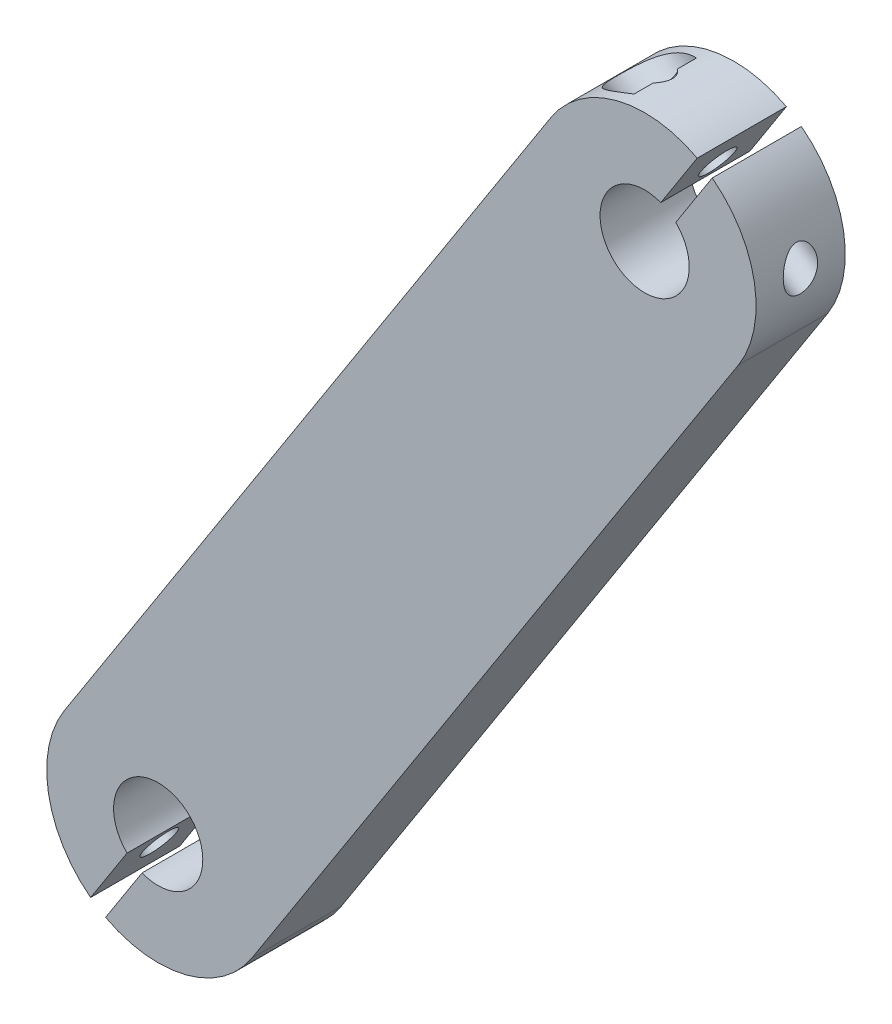
SolidWorks part; units mm, degrees
material "ALUMINUM 6061"
ref_plane "Front Plane" through (0, 0, 0) normal (0, 0, 1) x (1, 0, 0)
ref_plane "Top Plane" through (0, 0, 0) normal (0, 1, 0) x (1, 0, 0)
ref_plane "Right Plane" through (0, 0, 0) normal (1, 0, 0) x (0, 0, -1)
sketch "Sketch1" plane through (0, 0, 0) normal (0, 0, 1) x (1, 0, 0)
  line L0 (0, 0) -> (0, 177.8) construction
  line L3 (0, 177.8) -> (177.8, 177.8) construction
  line L4 (54.2644, 123.9224) -> (-25.4, 0) construction
  line L5 (54.2644, 123.9224) -> (88.9, 177.8) construction
  line L6 (47.5876, 128.2147) -> (82.2231, 182.0923)
  line L7 (60.9413, 119.6301) -> (95.5769, 173.5077)
  line L8 (-25.4, 0) -> (0, 0) construction
  arc A4 (47.5876, 128.2147) -> (60.9413, 119.6301) centre (54.2644, 123.9224) ccw
  arc A5 (95.5769, 173.5077) -> (82.2231, 182.0923) centre (88.9, 177.8) ccw
  circle A6 centre (88.9, 177.8) radius 3.175
  circle A7 centre (54.2644, 123.9224) radius 3.175
  point P2 (71.5822, 150.8612)
  dimension "D6" = 147.32
  dimension "D3" = 15.875
  dimension "D4" = 6.35
  dimension "D1" = 177.8
  dimension "D2" = 177.8
  dimension "D5" = 25.4
extrude "Boss-Extrude1" add sketch "Sketch1" along normal blind 6.35
sketch "Sketch2" plane through (0, 0, 6.35) normal (0, 0, 1) x (1, 0, 0)
  line L0 (92.6444, 184.7988) -> (90.0481, 180.7602)
  line L1 (91.1164, 180.0734) -> (93.7127, 184.1121)
  line L2 (52.048, 121.649) -> (49.4518, 117.6103)
  line L3 (53.1163, 120.9623) -> (50.5201, 116.9236)
  line L4 (82.2231, 182.0923) -> (47.5876, 128.2147) construction
  arc A4 (95.5769, 173.5077) -> (82.2231, 182.0923) centre (88.9, 177.8) ccw construction
  circle A5 centre (88.9, 177.8) radius 3.175 construction
  circle A6 centre (54.2644, 123.9224) radius 3.175 construction
  arc A7 (47.5876, 128.2147) -> (60.9413, 119.6301) centre (54.2644, 123.9224) ccw construction
  arc A8 (93.7127, 184.1121) -> (92.6444, 184.7988) centre (88.9, 177.8) ccw
  arc A9 (92.6444, 184.7988) -> (93.7127, 184.1121) centre (88.9, 177.8) ccw construction
  arc A10 (91.1164, 180.0734) -> (90.0481, 180.7602) centre (88.9, 177.8) ccw
  arc A11 (90.0481, 180.7602) -> (91.1164, 180.0734) centre (88.9, 177.8) ccw construction
  arc A12 (49.4518, 117.6103) -> (50.5201, 116.9236) centre (54.2644, 123.9224) ccw
  arc A13 (52.048, 121.649) -> (53.1163, 120.9623) centre (54.2644, 123.9224) ccw
  arc A14 (50.5201, 116.9236) -> (49.4518, 117.6103) centre (54.2644, 123.9224) ccw construction
  arc A15 (53.1163, 120.9623) -> (52.048, 121.649) centre (54.2644, 123.9224) ccw construction
  dimension "D1" = 1.27
extrude "Cut-Extrude1" cut sketch "Sketch2" against normal through all
hole_wizard "CBORE for #2 _1" positions "Sketch6" profile "Sketch3" counterbore size "#2" standard "ANSI Inch" end condition through all
sketch "Sketch6" plane through (-24.6494, 15.8461, 0) normal (-0.8412, 0.5408, 0) x (0, 0, 1)
  line L0 (3.175, 205.5469) -> (3.175, 202.3719) construction
  line L1 (0, 205.5469) -> (6.35, 205.5469) construction
  line L2 (3.175, 202.3719) -> (3.175, 128.8477) construction
  line L3 (3.175, 128.8477) -> (3.175, 125.6727) construction
  line L4 (0, 125.6727) -> (6.35, 125.6727) construction
  point P0 (3.175, 202.3719)
  point P2 (3.175, 128.8477)
  dimension "D1" = 3.175
sketch "Sketch3" plane through (84.7847, 186.077, 3.175) normal (0, 0, 1) x (-0.5408, -0.8412, 0)
  line L0 (0, 0) -> (0, 48.0413)
  line L1 (0, 48.0413) -> (1.2192, 48.0413)
  line L3 (1.2192, 48.0413) -> (1.2192, 2.3114)
  line L4 (1.2192, 2.3114) -> (2.3812, 2.3114)
  line L5 (2.3812, 2.3114) -> (2.3812, 0)
  line L7 (2.3812, 0) -> (0, 0)
  line L11 (0, -6.35) -> (0, 107.95) construction
  dimension "Thru Hole Dia." = 2.4384
  dimension "Thru Hole Depth" = 48.0413
  dimension "C'Bore Dia." = 4.7625
  dimension "C'Bore Depth" = 2.3114
move or copy body "Body-Move/Copy1" [suppressed] bodies to move or copy 103
